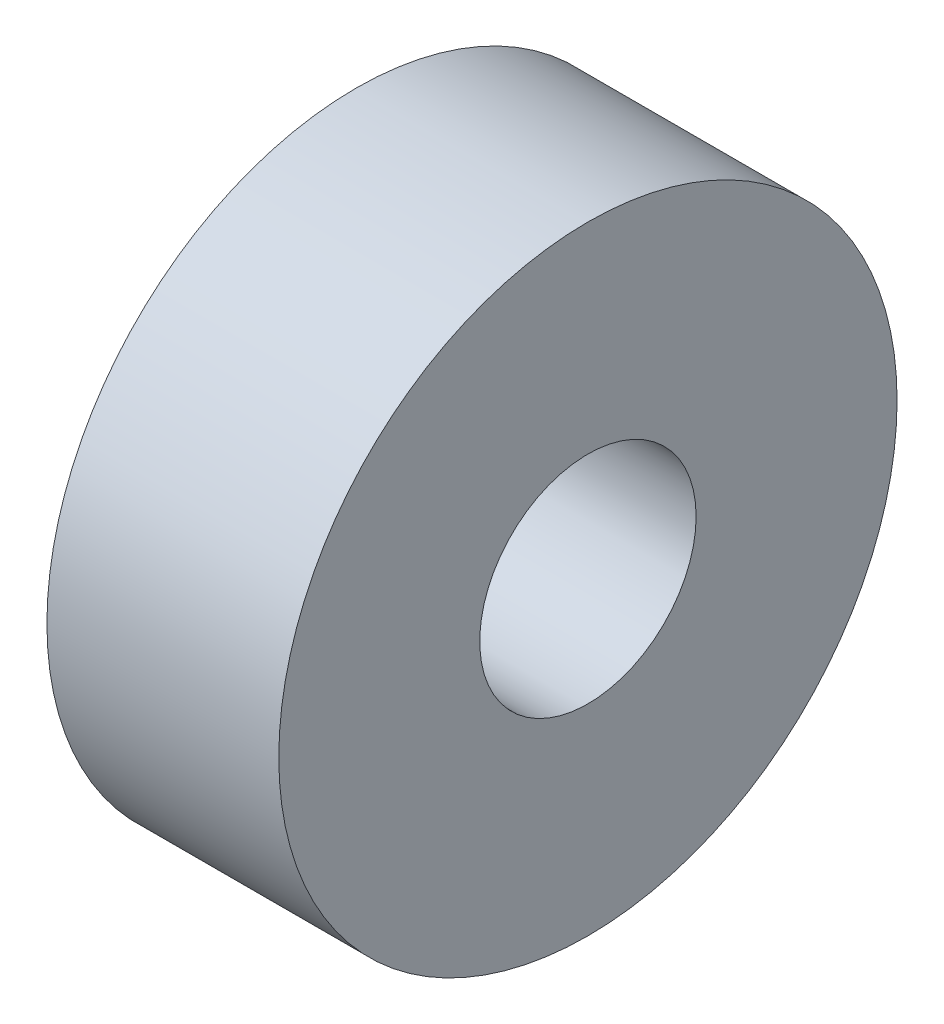
SolidWorks part; units mm, degrees
ref_plane "Alzado" through (0, 0, 0) normal (0, 0, 1) x (1, 0, 0)
ref_plane "Planta" through (0, 0, 0) normal (0, 1, 0) x (1, 0, 0)
ref_plane "Vista lateral" through (0, 0, 0) normal (1, 0, 0) x (0, 0, -1)
sketch "Croquis2" plane through (0, 0, 0) normal (1, 0, 0) x (0, 0, -1)
  circle A1 centre (0, 0) radius 1.4
  circle A4 centre (0, 0) radius 4
  dimension "D2" = 8
  dimension "D1" = 2.8
extrude "Saliente-Extruir1" add sketch "Croquis2" along normal blind 3
